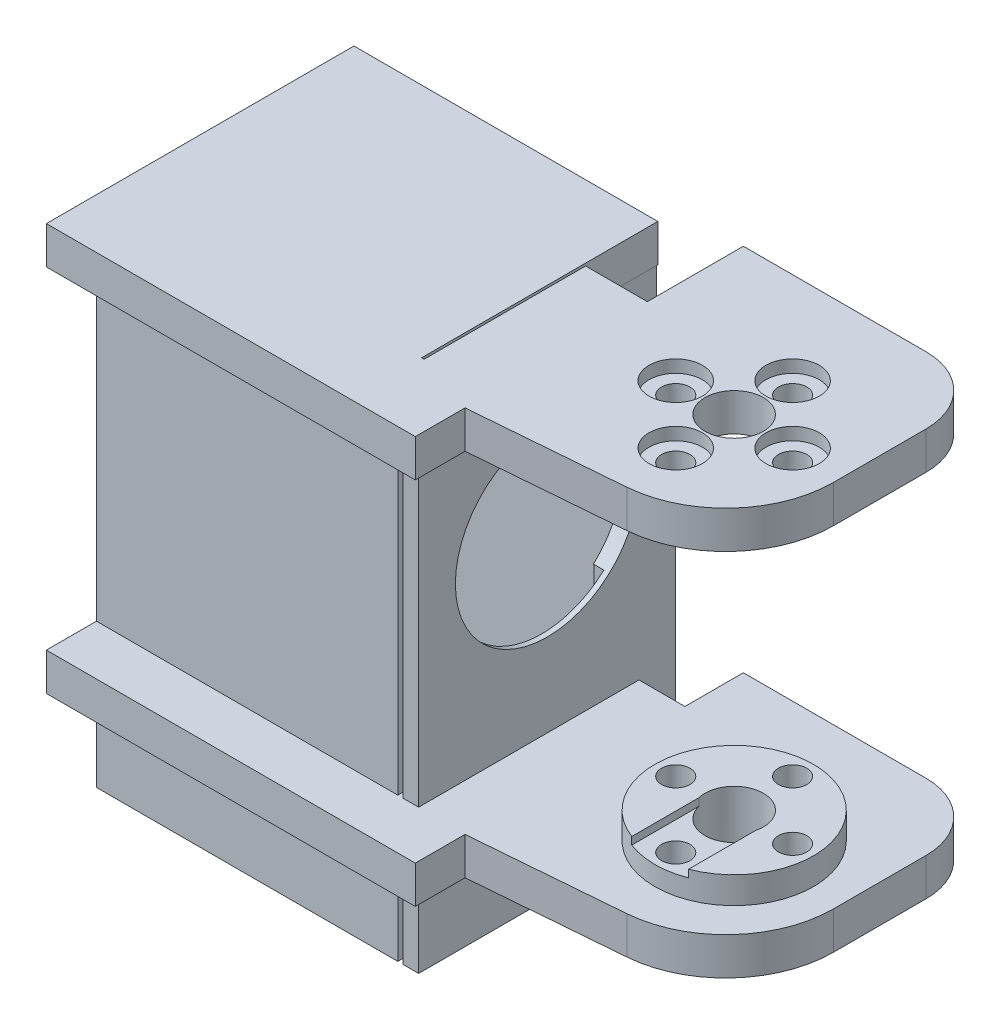
SolidWorks part; units mm, degrees
ref_plane "Front Plane" through (0, 0, 0) normal (0, 0, 1) x (1, 0, 0)
ref_plane "Top Plane" through (0, 0, 0) normal (0, 1, 0) x (1, 0, 0)
ref_plane "Right Plane" through (0, 0, 0) normal (1, 0, 0) x (0, 0, -1)
ref_plane "PY_p18_800" through (0, 18.8, 0) normal (0, 1, 0) x (1, 0, 0)
sketch "S_prism1" plane through (0, 18.8, 0) normal (0, 1, 0) x (1, 0, 0)
  line L0 (13, 10) -> (13, -1.1138)
  line L1 (1.1535, -13.9707) -> (-16.9, -15.45)
  line L2 (-16.9, -15.45) -> (-16.9, 18)
  line L3 (-16.9, 18) -> (5, 18)
  arc A0 (5, 18) -> (13, 10) centre (5.0002, 10.0002) cw
  arc A1 (13, -1.1138) -> (1.1535, -13.9707) centre (0.1, -1.1138) cw
extrude "Boss_1" add sketch "S_prism1" along normal blind 4.5
ref_plane "PY_m20_950" through (0, -20.95, 0) normal (0, 1, 0) x (1, 0, 0)
sketch "S_cyl2" plane through (0, -20.95, 0) normal (0, 1, 0) x (1, 0, 0)
  circle A0 centre (0, 0) radius 9.5
  dimension "D1_S_cyl2" = 19
extrude "Boss_2" add sketch "S_cyl2" along normal blind 3.2
ref_plane "PY_m25_450" through (0, -25.45, 0) normal (0, 1, 0) x (1, 0, 0)
sketch "S_prism3" plane through (0, -25.45, 0) normal (0, 1, 0) x (1, 0, 0)
  line L0 (13, 10) -> (13, -1.1138)
  line L1 (1.1535, -13.9707) -> (-16.9, -15.45)
  line L2 (-16.9, -15.45) -> (-16.9, 18)
  line L3 (-16.9, 18) -> (5, 18)
  arc A0 (5, 18) -> (13, 10) centre (5.0002, 10.0002) cw
  arc A1 (13, -1.1138) -> (1.1535, -13.9707) centre (0.1, -1.1138) cw
extrude "Boss_3" add sketch "S_prism3" along normal blind 4.5
sketch "S_prism4" plane through (0, 18.8, 0) normal (0, 1, 0) x (1, 0, 0)
  line L0 (-24.3, 6.5) -> (-16.8, 6.5)
  line L1 (-16.8, 6.5) -> (-16.8, -15.45)
  line L2 (-16.8, -15.45) -> (-24.3, -15.45)
  line L3 (-24.3, -15.45) -> (-24.3, 6.5)
extrude "Boss_4" add sketch "S_prism4" along normal blind 4.5
sketch "S_prism5" plane through (0, 18.8, 0) normal (0, 1, 0) x (1, 0, 0)
  line L0 (-61, -12.85) -> (-16.8, -12.85)
  line L1 (-16.8, -12.85) -> (-16.8, -21.4)
  line L2 (-16.8, -21.4) -> (-61, -21.4)
  line L3 (-61, -21.4) -> (-61, -12.85)
extrude "Boss_5" add sketch "S_prism5" along normal blind 4.5
sketch "S_prism6" plane through (0, 18.8, 0) normal (0, 1, 0) x (1, 0, 0)
  line L0 (-61, 15.45) -> (-24.6, 15.45)
  line L1 (-24.6, 15.45) -> (-24.6, -15.45)
  line L2 (-24.6, -15.45) -> (-61, -15.45)
  line L3 (-61, -15.45) -> (-61, 15.45)
extrude "Boss_6" add sketch "S_prism6" along normal blind 4.5
sketch "S_prism7" plane through (0, -25.45, 0) normal (0, 1, 0) x (1, 0, 0)
  line L0 (-24.3, 11) -> (-16.8, 11)
  line L1 (-16.8, 11) -> (-16.8, -15.45)
  line L2 (-16.8, -15.45) -> (-24.3, -15.45)
  line L3 (-24.3, -15.45) -> (-24.3, 11)
extrude "Boss_7" add sketch "S_prism7" along normal blind 4.5
sketch "S_prism8" plane through (0, -25.45, 0) normal (0, 1, 0) x (1, 0, 0)
  line L0 (-61, -12.85) -> (-16.8, -12.85)
  line L1 (-16.8, -12.85) -> (-16.8, -21.4)
  line L2 (-16.8, -21.4) -> (-61, -21.4)
  line L3 (-61, -21.4) -> (-61, -12.85)
extrude "Boss_8" add sketch "S_prism8" along normal blind 4.5
ref_plane "PZ_m15_400" through (0, 0, -15.4) normal (0, 0, 1) x (1, 0, 0)
sketch "S_box9" plane through (0, 0, -15.4) normal (0, 0, 1) x (1, 0, 0)
  line L0 (-61, 10.7) -> (-24.9, 10.7)
  line L1 (-24.9, 10.7) -> (-24.9, 13.2)
  line L2 (-24.9, 13.2) -> (-61, 13.2)
  line L3 (-61, 13.2) -> (-61, 10.7)
  dimension "P1" = 61
  dimension "P2" = 10.7
  dimension "P3" = 24.9
  dimension "P4" = 10.7
  dimension "P5" = 24.9
  dimension "P6" = 13.2
  dimension "P7" = 61
  dimension "P8" = 13.2
extrude "Boss_9" add sketch "S_box9" along normal blind 30.8
sketch "S_box10" plane through (0, 0, -15.4) normal (0, 0, 1) x (1, 0, 0)
  line L0 (-61, -38.2) -> (-24.9, -38.2)
  line L1 (-24.9, -38.2) -> (-24.9, 13.2)
  line L2 (-24.9, 13.2) -> (-61, 13.2)
  line L3 (-61, 13.2) -> (-61, -38.2)
  dimension "P1" = 61
  dimension "P2" = 38.2
  dimension "P3" = 24.9
  dimension "P4" = 38.2
  dimension "P5" = 24.9
  dimension "P6" = 13.2
  dimension "P7" = 61
  dimension "P8" = 13.2
extrude "Boss_10" add sketch "S_box10" along normal blind 2.5
ref_plane "PZ_p12_900" through (0, 0, 12.9) normal (0, 0, 1) x (1, 0, 0)
sketch "S_box11" plane through (0, 0, 12.9) normal (0, 0, 1) x (1, 0, 0)
  line L0 (-61, -38.2) -> (-24.9, -38.2)
  line L1 (-24.9, -38.2) -> (-24.9, 13.2)
  line L2 (-24.9, 13.2) -> (-61, 13.2)
  line L3 (-61, 13.2) -> (-61, -38.2)
  dimension "P1" = 61
  dimension "P2" = 38.2
  dimension "P3" = 24.9
  dimension "P4" = 38.2
  dimension "P5" = 24.9
  dimension "P6" = 13.2
  dimension "P7" = 61
  dimension "P8" = 13.2
extrude "Boss_11" add sketch "S_box11" along normal blind 2.5
sketch "S_box12" plane through (0, 0, -15.4) normal (0, 0, 1) x (1, 0, 0)
  line L0 (-61, -38.2) -> (-56.4, -38.2)
  line L1 (-56.4, -38.2) -> (-56.4, 13.2)
  line L2 (-56.4, 13.2) -> (-61, 13.2)
  line L3 (-61, 13.2) -> (-61, -38.2)
  dimension "P1" = 61
  dimension "P2" = 38.2
  dimension "P3" = 56.4
  dimension "P4" = 38.2
  dimension "P5" = 56.4
  dimension "P6" = 13.2
  dimension "P7" = 61
  dimension "P8" = 13.2
extrude "Boss_12" add sketch "S_box12" along normal blind 30.8
sketch "S_box13" plane through (0, 0, -15.4) normal (0, 0, 1) x (1, 0, 0)
  line L0 (-24.3, -38.2) -> (-22.4, -38.2)
  line L1 (-22.4, -38.2) -> (-22.4, 15.9)
  line L2 (-22.4, 15.9) -> (-24.3, 15.9)
  line L3 (-24.3, 15.9) -> (-24.3, -38.2)
  dimension "P1" = 24.3
  dimension "P2" = 38.2
  dimension "P3" = 22.4
  dimension "P4" = 38.2
  dimension "P5" = 22.4
  dimension "P6" = 15.9
  dimension "P7" = 24.3
  dimension "P8" = 15.9
extrude "Boss_13" add sketch "S_box13" along normal blind 30.8
ref_plane "PZ_m15_380" through (0, 0, -15.38) normal (0, 0, 1) x (1, 0, 0)
sketch "S_box14" plane through (0, 0, -15.38) normal (0, 0, 1) x (1, 0, 0)
  line L0 (-60.93, 12.9) -> (-24.67, 12.9)
  line L1 (-24.67, 12.9) -> (-24.67, 18.9)
  line L2 (-24.67, 18.9) -> (-60.93, 18.9)
  line L3 (-60.93, 18.9) -> (-60.93, 12.9)
  dimension "P1" = 60.93
  dimension "P2" = 12.9
  dimension "P3" = 24.67
  dimension "P4" = 12.9
  dimension "P5" = 24.67
  dimension "P6" = 18.9
  dimension "P7" = 60.93
  dimension "P8" = 18.9
extrude "Boss_14" add sketch "S_box14" along normal blind 30.76
ref_plane "PY_p18_700" through (0, 18.7, 0) normal (0, 1, 0) x (1, 0, 0)
sketch "S_hole15" plane through (0, 18.7, 0) normal (0, 1, 0) x (1, 0, 0)
  circle A0 centre (0, 0) radius 3.5
  dimension "D1_S_hole15" = 7
extrude "Hole_15" cut sketch "S_hole15" along normal blind 4.7
sketch "S_hole16" plane through (0, 18.7, 0) normal (0, 1, 0) x (1, 0, 0)
  circle A0 centre (7, 0) radius 1.7
  dimension "D1_S_hole16" = 3.4
  dimension "P2" = 7
extrude "Hole_16" cut sketch "S_hole16" along normal blind 4.7
sketch "S_hole17" plane through (0, 18.7, 0) normal (0, 1, 0) x (1, 0, 0)
  circle A0 centre (0, -7) radius 1.7
  dimension "D1_S_hole17" = 3.4
  dimension "P2" = 7
extrude "Hole_17" cut sketch "S_hole17" along normal blind 4.7
sketch "S_hole18" plane through (0, 18.7, 0) normal (0, 1, 0) x (1, 0, 0)
  circle A0 centre (-7, 0) radius 1.7
  dimension "D1_S_hole18" = 3.4
  dimension "P2" = 7
extrude "Hole_18" cut sketch "S_hole18" along normal blind 4.7
sketch "S_hole19" plane through (0, 18.7, 0) normal (0, 1, 0) x (1, 0, 0)
  circle A0 centre (0, 7) radius 1.7
  dimension "D1_S_hole19" = 3.4
  dimension "P2" = 7
extrude "Hole_19" cut sketch "S_hole19" along normal blind 4.7
ref_plane "PY_p21_800" through (0, 21.8, 0) normal (0, 1, 0) x (1, 0, 0)
sketch "S_hole20" plane through (0, 21.8, 0) normal (0, 1, 0) x (1, 0, 0)
  circle A0 centre (7, 0) radius 3.2
  dimension "D1_S_hole20" = 6.4
  dimension "P2" = 7
extrude "Hole_20" cut sketch "S_hole20" along normal blind 1.6
sketch "S_hole21" plane through (0, 21.8, 0) normal (0, 1, 0) x (1, 0, 0)
  circle A0 centre (0, -7) radius 3.2
  dimension "D1_S_hole21" = 6.4
  dimension "P2" = 7
extrude "Hole_21" cut sketch "S_hole21" along normal blind 1.6
sketch "S_hole22" plane through (0, 21.8, 0) normal (0, 1, 0) x (1, 0, 0)
  circle A0 centre (-7, 0) radius 3.2
  dimension "D1_S_hole22" = 6.4
  dimension "P2" = 7
extrude "Hole_22" cut sketch "S_hole22" along normal blind 1.6
sketch "S_hole23" plane through (0, 21.8, 0) normal (0, 1, 0) x (1, 0, 0)
  circle A0 centre (0, 7) radius 3.2
  dimension "D1_S_hole23" = 6.4
  dimension "P2" = 7
extrude "Hole_23" cut sketch "S_hole23" along normal blind 1.6
ref_plane "PY_m25_550" through (0, -25.55, 0) normal (0, 1, 0) x (1, 0, 0)
sketch "S_hole24" plane through (0, -25.55, 0) normal (0, 1, 0) x (1, 0, 0)
  circle A0 centre (0, 0) radius 3.5
  dimension "D1_S_hole24" = 7
extrude "Hole_24" cut sketch "S_hole24" along normal blind 7.9
sketch "S_hole25" plane through (0, -25.55, 0) normal (0, 1, 0) x (1, 0, 0)
  circle A0 centre (7, 0) radius 1.7
  dimension "D1_S_hole25" = 3.4
  dimension "P2" = 7
extrude "Hole_25" cut sketch "S_hole25" along normal blind 7.9
sketch "S_hole26" plane through (0, -25.55, 0) normal (0, 1, 0) x (1, 0, 0)
  circle A0 centre (0, -7) radius 1.7
  dimension "D1_S_hole26" = 3.4
  dimension "P2" = 7
extrude "Hole_26" cut sketch "S_hole26" along normal blind 7.9
sketch "S_hole27" plane through (0, -25.55, 0) normal (0, 1, 0) x (1, 0, 0)
  circle A0 centre (-7, 0) radius 1.7
  dimension "D1_S_hole27" = 3.4
  dimension "P2" = 7
extrude "Hole_27" cut sketch "S_hole27" along normal blind 7.9
sketch "S_hole28" plane through (0, -25.55, 0) normal (0, 1, 0) x (1, 0, 0)
  circle A0 centre (0, 7) radius 1.7
  dimension "D1_S_hole28" = 3.4
  dimension "P2" = 7
extrude "Hole_28" cut sketch "S_hole28" along normal blind 7.9
sketch "S_hole29" plane through (0, -25.55, 0) normal (0, 1, 0) x (1, 0, 0)
  circle A0 centre (7, 0) radius 3.2
  dimension "D1_S_hole29" = 6.4
  dimension "P2" = 7
extrude "Hole_29" cut sketch "S_hole29" along normal blind 2.1
sketch "S_hole30" plane through (0, -25.55, 0) normal (0, 1, 0) x (1, 0, 0)
  circle A0 centre (0, -7) radius 3.2
  dimension "D1_S_hole30" = 6.4
  dimension "P2" = 7
extrude "Hole_30" cut sketch "S_hole30" along normal blind 2.1
sketch "S_hole31" plane through (0, -25.55, 0) normal (0, 1, 0) x (1, 0, 0)
  circle A0 centre (-7, 0) radius 3.2
  dimension "D1_S_hole31" = 6.4
  dimension "P2" = 7
extrude "Hole_31" cut sketch "S_hole31" along normal blind 2.1
sketch "S_hole32" plane through (0, -25.55, 0) normal (0, 1, 0) x (1, 0, 0)
  circle A0 centre (0, 7) radius 3.2
  dimension "D1_S_hole32" = 6.4
  dimension "P2" = 7
extrude "Hole_32" cut sketch "S_hole32" along normal blind 2.1
sketch "S_cut33" plane through (0, 0, 0) normal (0, 0, 1) x (1, 0, 0)
  line L0 (-3.4, -18.65) -> (3.4, -18.65)
  line L1 (3.4, -18.65) -> (3.4, -17.65)
  line L2 (3.4, -17.65) -> (-3.4, -17.65)
  line L3 (-3.4, -17.65) -> (-3.4, -18.65)
  dimension "P1" = 3.4
  dimension "P2" = 18.65
  dimension "P3" = 3.4
  dimension "P4" = 18.65
  dimension "P5" = 3.4
  dimension "P6" = 17.65
  dimension "P7" = 3.4
  dimension "P8" = 17.65
extrude "Pocket_33" cut sketch "S_cut33" along normal blind 10
ref_plane "PX_m61_100" through (-61.1, 0, 0) normal (1, 0, 0) x (0, 0, -1)
sketch "S_hole34" plane through (-61.1, 0, 0) normal (1, 0, 0) x (0, 0, -1)
  circle A0 centre (0, 0) radius 10.5
  dimension "D1_S_hole34" = 21
extrude "Hole_34" cut sketch "S_hole34" along normal blind 4.8
ref_plane "PZ_m9_700" through (0, 0, -9.7) normal (0, 0, 1) x (1, 0, 0)
sketch "S_cut35" plane through (0, 0, -9.7) normal (0, 0, 1) x (1, 0, 0)
  line L0 (-61.1, -30.4) -> (-56.35, -30.4)
  line L1 (-56.35, -30.4) -> (-56.35, -10.9)
  line L2 (-56.35, -10.9) -> (-61.1, -10.9)
  line L3 (-61.1, -10.9) -> (-61.1, -30.4)
  dimension "P1" = 61.1
  dimension "P2" = 30.4
  dimension "P3" = 56.35
  dimension "P4" = 30.4
  dimension "P5" = 56.35
  dimension "P6" = 10.9
  dimension "P7" = 61.1
  dimension "P8" = 10.9
extrude "Pocket_35" cut sketch "S_cut35" along normal blind 19.4
sketch "S_cut36" plane through (0, 0, -9.7) normal (0, 0, 1) x (1, 0, 0)
  line L0 (-61.1, -38.7) -> (-56.35, -38.7)
  line L1 (-56.35, -38.7) -> (-56.35, -30.4)
  line L2 (-56.35, -30.4) -> (-61.1, -30.4)
  line L3 (-61.1, -30.4) -> (-61.1, -38.7)
  dimension "P1" = 61.1
  dimension "P2" = 38.7
  dimension "P3" = 56.35
  dimension "P4" = 38.7
  dimension "P5" = 56.35
  dimension "P6" = 30.4
  dimension "P7" = 61.1
  dimension "P8" = 30.4
extrude "Pocket_36" cut sketch "S_cut36" along normal blind 19.4
ref_plane "PZ_m3_500" through (0, 0, -3.5) normal (0, 0, 1) x (1, 0, 0)
sketch "S_cut37" plane through (0, 0, -3.5) normal (0, 0, 1) x (1, 0, 0)
  line L0 (-61.1, -11) -> (-56.35, -11)
  line L1 (-56.35, -11) -> (-56.35, 0)
  line L2 (-56.35, 0) -> (-61.1, 0)
  line L3 (-61.1, 0) -> (-61.1, -11)
  dimension "P1" = 61.1
  dimension "P2" = 11
  dimension "P3" = 56.35
  dimension "P4" = 11
  dimension "P5" = 56.35
  dimension "P6" = 61.1
extrude "Pocket_37" cut sketch "S_cut37" along normal blind 7
ref_plane "PZ_m15_900" through (0, 0, -15.9) normal (0, 0, 1) x (1, 0, 0)
sketch "S_cut38" plane through (0, 0, -15.9) normal (0, 0, 1) x (1, 0, 0)
  line L0 (-61.2, -10) -> (-58.3, -10)
  line L1 (-58.3, -10) -> (-58.3, 10)
  line L2 (-58.3, 10) -> (-61.2, 10)
  line L3 (-61.2, 10) -> (-61.2, -10)
  dimension "P1" = 61.2
  dimension "P2" = 10
  dimension "P3" = 58.3
  dimension "P4" = 10
  dimension "P5" = 58.3
  dimension "P6" = 10
  dimension "P7" = 61.2
  dimension "P8" = 10
extrude "Pocket_38" cut sketch "S_cut38" along normal blind 15.9
sketch "S_hole39" plane through (-61.1, 0, 0) normal (1, 0, 0) x (0, 0, -1)
  circle A0 centre (-10.25, -8.3) radius 1.1
  dimension "D1_S_hole39" = 2.2
  dimension "P2" = 10.25
  dimension "P3" = 8.3
extrude "Hole_39" cut sketch "S_hole39" along normal blind 4.8
sketch "S_hole40" plane through (-61.1, 0, 0) normal (1, 0, 0) x (0, 0, -1)
  circle A0 centre (-10.25, -8.3) radius 2.3
  dimension "D1_S_hole40" = 4.6
  dimension "P2" = 10.25
  dimension "P3" = 8.3
extrude "Hole_40" cut sketch "S_hole40" along normal blind 1.7
sketch "S_hole41" plane through (-61.1, 0, 0) normal (1, 0, 0) x (0, 0, -1)
  circle A0 centre (10.25, -32.75) radius 1.1
  dimension "D1_S_hole41" = 2.2
  dimension "P2" = 10.25
  dimension "P3" = 32.75
extrude "Hole_41" cut sketch "S_hole41" along normal blind 4.8
sketch "S_hole42" plane through (-61.1, 0, 0) normal (1, 0, 0) x (0, 0, -1)
  circle A0 centre (10.25, -32.75) radius 2.3
  dimension "D1_S_hole42" = 4.6
  dimension "P2" = 10.25
  dimension "P3" = 32.75
extrude "Hole_42" cut sketch "S_hole42" along normal blind 1.7
sketch "S_hole43" plane through (-61.1, 0, 0) normal (1, 0, 0) x (0, 0, -1)
  circle A0 centre (-10.25, -32.75) radius 1.1
  dimension "D1_S_hole43" = 2.2
  dimension "P2" = 10.25
  dimension "P3" = 32.75
extrude "Hole_43" cut sketch "S_hole43" along normal blind 4.8
sketch "S_hole44" plane through (-61.1, 0, 0) normal (1, 0, 0) x (0, 0, -1)
  circle A0 centre (-10.25, -32.75) radius 2.3
  dimension "D1_S_hole44" = 4.6
  dimension "P2" = 10.25
  dimension "P3" = 32.75
extrude "Hole_44" cut sketch "S_hole44" along normal blind 1.7
ref_plane "PX_m25_000" through (-25, 0, 0) normal (1, 0, 0) x (0, 0, -1)
sketch "S_hole45" plane through (-25, 0, 0) normal (1, 0, 0) x (0, 0, -1)
  circle A0 centre (0, 0) radius 11
  dimension "D1_S_hole45" = 22
extrude "Hole_45" cut sketch "S_hole45" along normal blind 2.7
ref_plane "PZ_m7_500" through (0, 0, -7.5) normal (0, 0, 1) x (1, 0, 0)
sketch "S_cut46" plane through (0, 0, -7.5) normal (0, 0, 1) x (1, 0, 0)
  line L0 (-24.9, -38.7) -> (-23.05, -38.7)
  line L1 (-23.05, -38.7) -> (-23.05, -8.1)
  line L2 (-23.05, -8.1) -> (-24.9, -8.1)
  line L3 (-24.9, -8.1) -> (-24.9, -38.7)
  dimension "P1" = 24.9
  dimension "P2" = 38.7
  dimension "P3" = 23.05
  dimension "P4" = 38.7
  dimension "P5" = 23.05
  dimension "P6" = 8.1
  dimension "P7" = 24.9
  dimension "P8" = 8.1
extrude "Pocket_46" cut sketch "S_cut46" along normal blind 15
sketch "S_pcut47" plane through (-61.1, 0, 0) normal (1, 0, 0) x (0, 0, -1)
  line L0 (16, -38.8) -> (16, -28.6)
  line L1 (16, -28.6) -> (5.8, -38.8)
  line L2 (5.8, -38.8) -> (16, -38.8)
extrude "Cut_47" cut sketch "S_pcut47" along normal blind 36.3
equation "\"plate_t\" = 3"
equation "\"clearance\" = 0.5"
